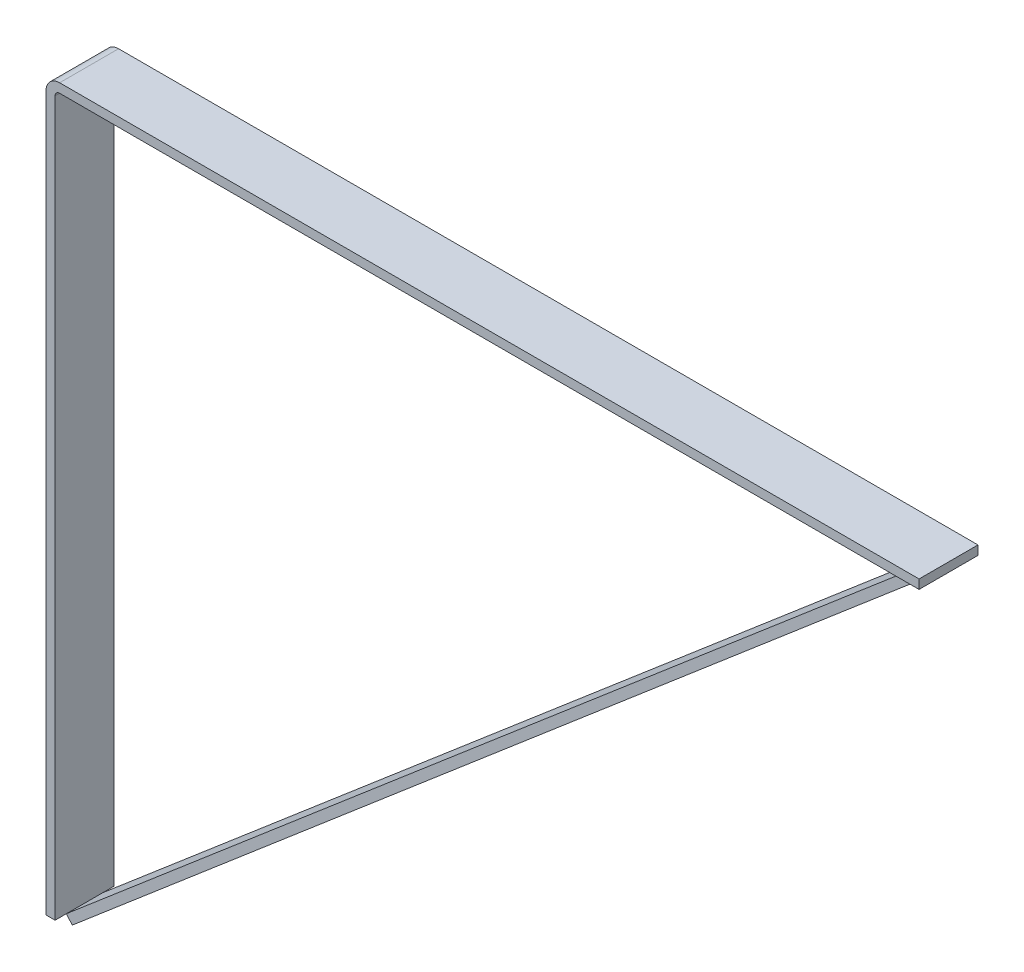
SolidWorks part; units mm, degrees
ref_plane "Front Plane" through (0, 0, 0) normal (0, 0, 1) x (1, 0, 0)
ref_plane "Top Plane" through (0, 0, 0) normal (0, 1, 0) x (1, 0, 0)
ref_plane "Right Plane" through (0, 0, 0) normal (1, 0, 0) x (0, 0, -1)
sketch "Sketch1" plane through (0, 0, 0) normal (0, 0, 1) x (1, 0, 0)
  line L0 (-309.5625, -508) -> (-309.5625, -9.525)
  line L1 (-300.0375, 0) -> (300.0375, 0)
  arc A0 (-309.5625, -9.525) -> (-300.0375, 0) centre (-300.0375, -9.525) cw
  point P6 (-309.5625, 0)
  dimension "D1" = 9.525
  dimension "LG" = 609.6
  dimension "HT" = 508
extrude "Extrude-Thin1" add sketch "Sketch1" along normal mid plane 41.148 thin
sketch "Sketch2" plane through (0, 0, 0) normal (0, 0, 1) x (1, 0, 0)
  line L0 (285.2504, -6.35) -> (-303.2125, -508)
  line L1 (-303.2125, -508) -> (-299.093, -512.8324)
  line L2 (-299.093, -512.8324) -> (295.0386, -6.35)
  line L3 (285.2504, -6.35) -> (295.0386, -6.35)
  line L4 (-300.0375, -6.35) -> (300.0375, -6.35) construction
  point P1 (-181.7061, -143.5016)
  point P9 (-207.1234, -152.4)
  point P10 (295.0386, -6.35)
  dimension "D1" = 6.35
extrude "Boss-Extrude1" add sketch "Sketch2" along normal mid plane 25.4 separate body
